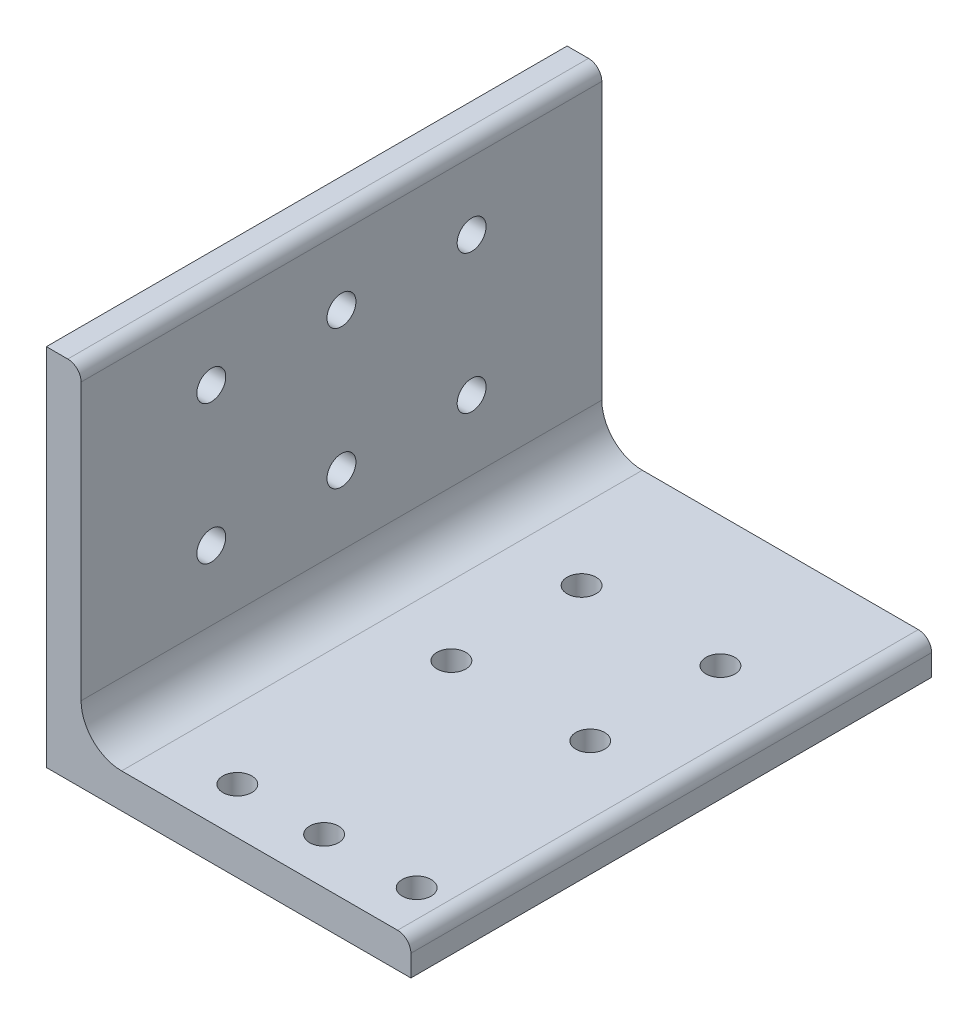
SolidWorks part; units mm, degrees
material "Сталь 3 ГОСТ 535-88"
ref_plane "Front Plane" through (0, 0, 0) normal (0, 0, 1) x (1, 0, 0)
ref_plane "Top Plane" through (0, 0, 0) normal (0, 1, 0) x (1, 0, 0)
ref_plane "Right Plane" through (0, 0, 0) normal (1, 0, 0) x (0, 0, -1)
sketch "Skizze2" plane through (0, 0, 0) normal (0, 0, 1) x (1, 0, 0)
  line L0 (0, 0) -> (63, 0)
  line L1 (0, 0) -> (0, 63)
  line L2 (0, 63) -> (3.7, 63)
  line L3 (6, 60.7) -> (6, 13)
  line L4 (0, 0) -> (63, 0)
  line L5 (13, 6) -> (60.7, 6)
  line L6 (63, 0) -> (63, 3.7)
  arc A2 (63, 3.7) -> (60.7, 6) centre (60.7, 3.7) ccw
  arc A3 (6, 60.7) -> (3.7, 63) centre (3.7, 60.7) ccw
  arc A4 (6, 13) -> (13, 6) centre (13, 13) ccw
extrude "Aufsatz-Linear austragen1" add sketch "Skizze2" along normal blind 90 contours A4 L3 A3 L2 L1 L0 L6 A2 L5
sketch "Skizze3" plane through (6, 0, 0) normal (1, 0, 0) x (0, 0, -1)
  line L4 (-67.5, 49) -> (-22.5, 49)
  line L5 (-67.5, 25) -> (-22.5, 25)
  line L6 (-45, 49) -> (-45, 25)
  line L7 (-90, 0) -> (0, 0) construction
  line L12 (-90, 0) -> (0, 0)
  line L14 (-41.374, 0) -> (-41.374, 25)
  line L15 (-90, 63) -> (0, 63) construction
  line L18 (-90, 63) -> (0, 63)
  line L19 (-38.9248, 63) -> (-38.9248, 49)
  point P5 (-45, 37)
  point P7 (-45, 25)
  point P8 (-45, 49)
  point P17 (-22.5, 36.85)
  point P18 (-67.5, 36.85)
  point P24 (-67.5, 49)
  point P25 (-22.5, 49)
  point P26 (-22.5, 25)
  point P27 (-67.5, 25)
hole_wizard "Ø5.0 (5) Durchmesser Bohrung1" positions "3D-Skizze2" profile "Skizze5" hole size "Ø5.0" standard "DIN" end condition through all
sketch3d "3D-Skizze2"
  point P0 (6, 25, 67.5)
  point P3 (6, 49, 67.5)
  point P6 (6, 49, 45)
  point P9 (6, 25, 45)
  point P12 (6, 25, 22.5)
  point P15 (6, 49, 22.5)
sketch "Skizze5" plane through (6, 25, 67.5) normal (0, 1, 0) x (0, 0, -1)
  line L0 (0, 0) -> (0, 6)
  line L1 (0, 6) -> (2.5, 6)
  line L2 (2.5, 6) -> (2.5, 0)
  line L5 (2.5, 0) -> (0, 0)
  line L11 (0, -6.35) -> (0, 107.95) construction
  dimension "Bohrerdurchmesser" = 5
  dimension "Bohrungstiefe" = 6
sketch "Skizze6" plane through (0, 6, 0) normal (0, 1, 0) x (1, 0, 0)
  line L0 (60.7, -45) -> (13, -45)
  line L1 (36.85, -90) -> (36.85, 0)
  line L2 (36.85, 0) -> (36.85, -90)
  line L3 (36.85, -67.5) -> (60.7, -67.5)
  line L5 (0, -90) -> (0, 0)
  line L7 (63, -90) -> (63, 0)
  line L8 (60.7, 0) -> (13, 0)
  line L9 (13, 0) -> (13, -89.25)
  line L10 (13, -89.25) -> (60.7, -89.25)
  line L11 (60.7, -89.25) -> (60.7, 0)
  line L12 (36.85, -22.5) -> (60.7, -22.5)
  line L13 (36.85, -22.5) -> (13, -22.5)
  line L14 (36.85, -67.5) -> (13, -67.5)
  line L15 (25, -22.5) -> (25, -67.5)
  line L16 (49, -22.5) -> (49, -67.5)
  line L17 (63, -31.8256) -> (49, -31.8256)
  line L18 (0, -37.1466) -> (25, -37.1466)
  line L19 (36.85, -8) -> (13, -8)
  line L20 (13, -16.75) -> (60.7, -16.75)
  line L21 (13, -8) -> (60.7, -8)
  line L22 (19.3849, 0) -> (19.3849, -8)
  line L23 (36.85, -8) -> (60.7, -8)
  line L24 (48.775, -8) -> (48.775, -16.75)
  line L25 (63, -7.0918) -> (48, -7.0918)
  line L26 (48, -7.0918) -> (48, -9.4032)
  line L27 (60.7, -8) -> (55.7, -8)
  line L28 (63, -4.943) -> (40, -4.943)
  line L29 (24.925, -8) -> (39.925, -8)
  line L30 (40, -4.943) -> (40, -10.8867)
  line L31 (63, -5.6635) -> (56, -5.6635)
  line L32 (56, -5.6635) -> (56, -9.8035)
  line L33 (63, -4.1211) -> (25, -4.1211)
  line L34 (25, -4.1211) -> (25, -8.3568)
  line L35 (63, -45) -> (9.8848, -45) construction
  line L36 (25, -85.8789) -> (25, -81.6432)
  line L37 (63, -85.8789) -> (25, -85.8789)
  line L38 (56, -84.3365) -> (56, -80.1965)
  line L39 (63, -84.3365) -> (56, -84.3365)
  line L40 (40, -85.057) -> (40, -79.1133)
  line L41 (24.925, -82) -> (39.925, -82)
  line L42 (63, -85.057) -> (40, -85.057)
  line L43 (60.7, -82) -> (55.7, -82)
  line L44 (48, -82.9082) -> (48, -80.5968)
  line L45 (63, -82.9082) -> (48, -82.9082)
  line L46 (48.775, -82) -> (48.775, -73.25)
  line L47 (36.85, -82) -> (60.7, -82)
  line L48 (19.3849, -90) -> (19.3849, -82)
  line L49 (13, -82) -> (60.7, -82)
  line L50 (13, -73.25) -> (60.7, -73.25)
  line L51 (36.85, -82) -> (13, -82)
  line L52 (0, -52.8534) -> (25, -52.8534)
  line L53 (63, -58.1744) -> (49, -58.1744)
  line L54 (36.85, -22.5) -> (13, -22.5)
  line L55 (36.85, -67.5) -> (13, -67.5)
  line L56 (36.85, -67.5) -> (60.7, -67.5)
  line L57 (60.7, -0.75) -> (60.7, -90)
  line L58 (13, -0.75) -> (60.7, -0.75)
  line L59 (13, -90) -> (13, -0.75)
  line L60 (60.7, -90) -> (13, -90)
  line L61 (36.85, -22.5) -> (60.7, -22.5)
  circle A0 centre (48, -8) radius 1.65
  circle A1 centre (48, -82) radius 1.65
  point P19 (25, -45)
  point P20 (49, -45)
  point P21 (25, -67.5)
  point P38 (25, -8)
  point P44 (48, -8)
  point P48 (49, -67.5)
  point P61 (40, -8)
  point P62 (56, -8)
  point P68 (56, -82)
  point P69 (40, -82)
  point P70 (25, -82)
  point P103 (36.85, -45)
hole_wizard "Ø5.0 (5) Durchmesser Bohrung2" positions "3D-Skizze4" profile "Skizze8" hole size "Ø5.0" standard "DIN" end condition through all
sketch3d "3D-Skizze4"
  point P0 (56, 6, 82)
  point P3 (40, 6, 82)
  point P6 (25, 6, 22.5)
  point P9 (49, 6, 22.5)
  point P12 (49, 6, 45)
  point P15 (25, 6, 45)
  point P18 (25, 6, 82)
sketch "Skizze8" plane through (56, 6, 82) normal (1, 0, 0) x (0, 0, 1)
  line L0 (0, 0) -> (0, 6)
  line L1 (0, 6) -> (2.5, 6)
  line L2 (2.5, 6) -> (2.5, 0)
  line L5 (2.5, 0) -> (0, 0)
  line L11 (0, -6.35) -> (0, 107.95) construction
  dimension "Bohrerdurchmesser" = 5
  dimension "Bohrungstiefe" = 6
